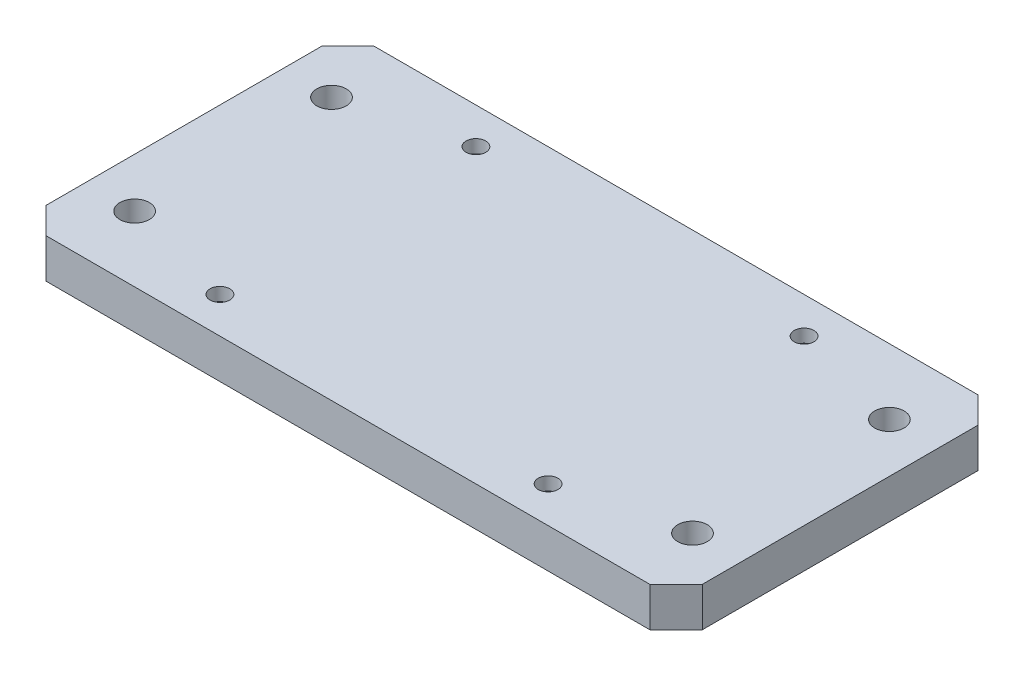
SolidWorks part; units mm, degrees
ref_plane "Front" through (0, 0, 0) normal (0, 0, 1) x (1, 0, 0)
ref_plane "Top" through (0, 0, 0) normal (0, 1, 0) x (1, 0, 0)
ref_plane "Right" through (0, 0, 0) normal (1, 0, 0) x (0, 0, -1)
sketch "Sketch1" plane through (0, 0, 0) normal (0, 1, 0) x (1, 0, 0)
  line L0 (11.3189, 0) -> (-205.4191, 0) construction
  line L1 (-200, 50) -> (0, 50)
  line L2 (-200, 50) -> (-200, -50)
  line L3 (-200, -50) -> (0, -50)
  line L4 (0, 50) -> (0, -50)
  dimension "D1" = 200
  dimension "D2" = 100
extrude "Boss-Extrude1" add sketch "Sketch1" along normal blind 12
hole_wizard "Ø9.0 (9) Diameter Hole1" positions "Sketch3" profile "Sketch2" hole size "Ø9.0" standard "JIS" end condition through all
sketch "Sketch3" plane through (0, 12, 0) normal (0, 1, 0) x (-1, 0, 0)
  line L3 (-11.7763, 0) -> (218.8908, 0) construction
  line L4 (0, 50) -> (0, -50) construction
  point P0 (185, 30)
  point P1 (15, 30)
  point P3 (15, -30)
  point P5 (185, -30)
  dimension "D1" = 15
  dimension "D2" = 60
  dimension "D3" = 170
sketch "Sketch2" plane through (-185, 12, 30) normal (1, 0, 0) x (0, 0, 1)
  line L0 (0, 0) -> (0, 12)
  line L1 (0, 12) -> (4.5, 12)
  line L2 (4.5, 12) -> (4.5, 0)
  line L5 (4.5, 0) -> (0, 0)
  line L11 (0, -6.35) -> (0, 107.95) construction
  dimension "Thru Hole Dia." = 9
  dimension "Thru Hole Depth" = 12
hole_wizard "CBORE for M5 Socket Head Cap Screw1" positions "Sketch5" profile "Sketch4" counterbore size "M5" standard "JIS" end condition through all
sketch "Sketch5" plane through (0, 0, 0) normal (0, -1, 0) x (1, 0, 0)
  line L4 (11.2756, 0) -> (-220.1155, 0) construction
  line L7 (0, 50) -> (0, -50) construction
  point P0 (-150, 39)
  point P1 (-50, 39)
  point P3 (-150, -39)
  point P5 (-50, -39)
  dimension "D1" = 100
  dimension "D2" = 78
  dimension "D3" = 50
sketch "Sketch4" plane through (-150, 0, 39) normal (1, 0, 0) x (0, 0, -1)
  line L0 (0, 0) -> (0, 12)
  line L1 (0, 12) -> (3, 12)
  line L3 (3, 12) -> (3, 8)
  line L4 (3, 8) -> (5.5, 8)
  line L5 (5.5, 8) -> (5.5, 0)
  line L7 (5.5, 0) -> (0, 0)
  line L11 (0, -6.35) -> (0, 107.95) construction
  dimension "Thru Hole Dia." = 6
  dimension "Thru Hole Depth" = 12
  dimension "C'Bore Dia." = 11
  dimension "C'Bore Depth" = 8
chamfer "Chamfer1" distance 8 4 edges at (0, 6, 50) (0, 6, -50) (-200, 6, -50) (-200, 6, 50)
